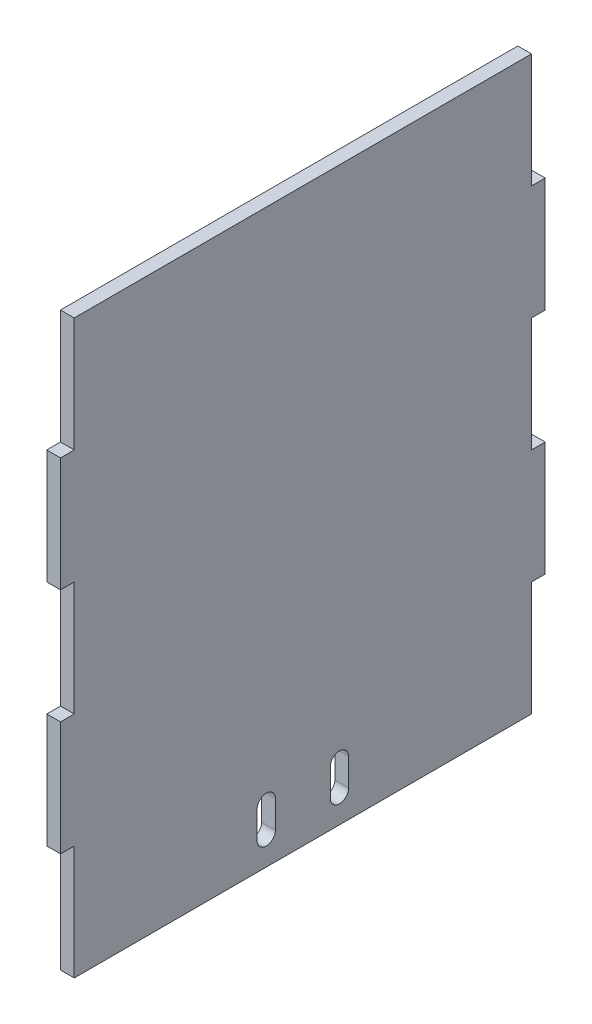
SolidWorks part; units mm, degrees
ref_plane "Front" through (0, 0, 0) normal (0, 0, 1) x (1, 0, 0)
ref_plane "Top" through (0, 0, 0) normal (0, 1, 0) x (1, 0, 0)
ref_plane "Right" through (0, 0, 0) normal (1, 0, 0) x (0, 0, -1)
sketch "Croquis1" plane through (0, 0, 0) normal (1, 0, 0) x (0, 0, -1)
  line L0 (-46.5171, 28.1963) -> (53.4829, 28.1963)
  line L10 (53.4829, -96.8037) -> (-46.5171, -96.8037)
  line L11 (3.4829, 28.1963) -> (3.4829, -96.8037) construction
  line L21 (53.4829, 28.1963) -> (53.4829, 3.1963)
  line L22 (53.4829, 3.1963) -> (56.4829, 3.1963)
  line L23 (56.4829, 3.1963) -> (56.4829, -21.8037)
  line L24 (56.4829, -21.8037) -> (53.4829, -21.8037)
  line L25 (53.4829, -21.8037) -> (53.4829, -46.8037)
  line L26 (53.4829, -46.8037) -> (56.4829, -46.8037)
  line L27 (56.4829, -46.8037) -> (56.4829, -71.8037)
  line L28 (56.4829, -71.8037) -> (53.4829, -71.8037)
  line L29 (53.4829, -96.8037) -> (53.4829, -71.8037)
  line L30 (-46.5171, -96.8037) -> (-46.5171, -71.8037)
  line L31 (-49.5171, -71.8037) -> (-46.5171, -71.8037)
  line L32 (-49.5171, -46.8037) -> (-49.5171, -71.8037)
  line L33 (-46.5171, -46.8037) -> (-49.5171, -46.8037)
  line L34 (-46.5171, -21.8037) -> (-46.5171, -46.8037)
  line L35 (-49.5171, -21.8037) -> (-46.5171, -21.8037)
  line L36 (-49.5171, 3.1963) -> (-49.5171, -21.8037)
  line L37 (-46.5171, 3.1963) -> (-49.5171, 3.1963)
  line L38 (-46.5171, 28.1963) -> (-46.5171, 3.1963)
  dimension "D1" = 100
  dimension "D2" = 100
  dimension "D3" = 25
  dimension "D4" = 25
  dimension "D5" = 3
  dimension "D6" = 25
  dimension "D7" = 2
extrude "Saliente-Extruir1" add sketch "Croquis1" along normal blind 3
sketch "Croquis2" plane through (3, 0, 0) normal (1, 0, 0) x (0, 0, -1)
  line L0 (3.4829, 28.1963) -> (3.4829, -96.8037) construction
  line L1 (53.4829, 28.1963) -> (-46.5171, 28.1963) construction
  line L2 (-46.5171, -96.8037) -> (53.4829, -96.8037) construction
  line L3 (-4.5171, -90.8037) -> (-4.5171, -84.8037) construction
  line L4 (-6.5171, -90.8037) -> (-6.5171, -84.8037)
  line L5 (-2.5171, -90.8037) -> (-2.5171, -84.8037)
  line L6 (11.4829, -90.8037) -> (11.4829, -84.8037) construction
  line L7 (13.4829, -90.8037) -> (13.4829, -84.8037)
  line L8 (9.4829, -90.8037) -> (9.4829, -84.8037)
  line L9 (3.4829, -96.8037) -> (-46.5171, -96.8037) construction
  arc A0 (-6.5171, -90.8037) -> (-2.5171, -90.8037) centre (-4.5171, -90.8037) ccw
  arc A1 (-2.5171, -84.8037) -> (-6.5171, -84.8037) centre (-4.5171, -84.8037) ccw
  arc A2 (13.4829, -90.8037) -> (9.4829, -90.8037) centre (11.4829, -90.8037) cw
  arc A3 (9.4829, -84.8037) -> (13.4829, -84.8037) centre (11.4829, -84.8037) cw
  point P8 (-4.5171, -87.8037)
  point P15 (11.4829, -87.8037)
  point P20 (-4.5171, -92.8037)
  point P23 (-4.5171, -82.8037)
  dimension "D1" = 2
  dimension "D3" = 10
  dimension "D2" = 6
  dimension "D4" = 20
extrude "Cortar-Extruir1" cut sketch "Croquis2" against normal blind 3
